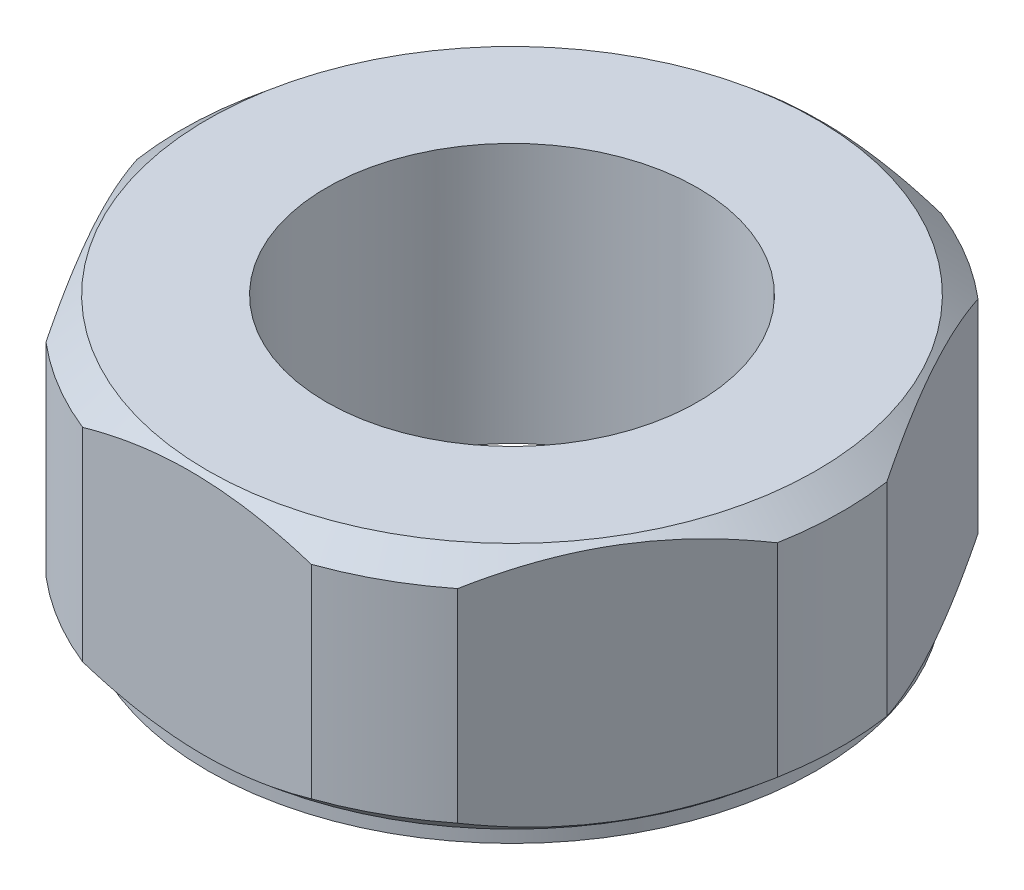
SolidWorks part; units mm, degrees
ref_plane "Front Plane" through (0, 0, 0) normal (0, 0, 1) x (1, 0, 0)
ref_plane "Top Plane" through (0, 0, 0) normal (0, 1, 0) x (1, 0, 0)
ref_plane "Right Plane" through (0, 0, 0) normal (1, 0, 0) x (0, 0, -1)
sketch "Sketch1" plane through (0, 0, 0) normal (0, 1, 0) x (1, 0, 0)
  line L1 (-1.3968, 2.5263) -> (-2.8863, 0.0535)
  line L2 (-2.8863, 0.0535) -> (-1.4895, -2.4728)
  line L3 (-1.4895, -2.4728) -> (1.3968, -2.5263)
  line L4 (1.3968, -2.5263) -> (2.8863, -0.0535)
  line L5 (2.8863, -0.0535) -> (1.4895, 2.4728)
  line L6 (1.4895, 2.4728) -> (-1.3968, 2.5263)
  circle A0 centre (0, 0) radius 2.5 construction
  dimension "D1" = 5
extrude "Boss-Extrude1" add sketch "Sketch1" along normal blind 2
sketch "Sketch2" plane through (0, 0, 0) normal (0, -1, 0) x (1, 0, 0)
  circle A0 centre (0, 0) radius 1.5
  dimension "D1" = 3
extrude "Cut-Extrude1" cut sketch "Sketch2" against normal blind 2.2
sketch "Sketch3" plane through (0, 0, 0) normal (1, 0, 0) x (0, 0, -1)
  line L0 (2.3175, 2.1202) -> (2.6714, 1.8207)
  line L1 (-0.0535, 1) -> (3.33, 1) construction
  line L2 (-0.0535, 2) -> (-0.0535, 0) construction
  line L3 (2.3175, -0.1202) -> (2.6714, 0.1793)
  line L4 (2.3175, 2.1202) -> (3.6415, 2.4454)
  line L5 (3.6415, 2.4454) -> (3.5856, -0.3042)
  line L6 (3.5856, -0.3042) -> (2.3175, -0.1202)
  line L7 (2.6714, 1.8207) -> (2.6714, 0.1793)
  line L8 (0, 0) -> (0, 2.0716) construction
revolve "Cut-Revolve1" cut sketch "Sketch3" angle 360 about L8
sketch "Sketch4" plane through (0, 0, 0) normal (0, -1, 0) x (1, 0, 0)
  circle A0 centre (0, 0) radius 1.5 construction
  circle A1 centre (0, 0) radius 2.4595
  circle A2 centre (0, 0) radius 2.4595
  circle A3 centre (0, 0) radius 1.5
  dimension "D1" = 0
extrude "Boss-Extrude2" add sketch "Sketch4" along normal blind 0.1
